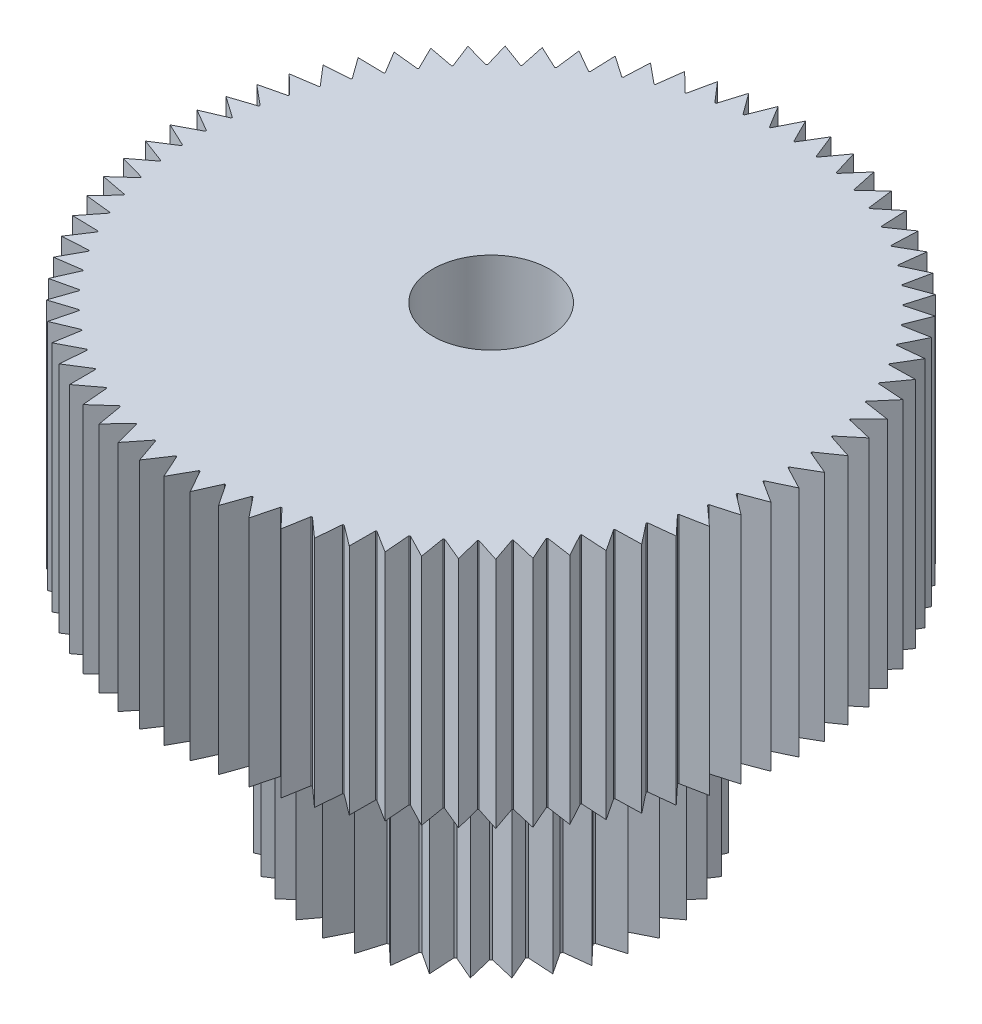
SolidWorks part; units mm, degrees
ref_plane "Front Plane" through (0, 0, 0) normal (0, 0, 1) x (1, 0, 0)
ref_plane "Top Plane" through (0, 0, 0) normal (0, 1, 0) x (1, 0, 0)
ref_plane "Right Plane" through (0, 0, 0) normal (1, 0, 0) x (0, 0, -1)
sketch "Sketch1" plane through (0, 0, 0) normal (0, 1, 0) x (1, 0, 0)
  circle A0 centre (0, 0) radius 5
  dimension "D1" = 10
extrude "Boss-Extrude1" add sketch "Sketch1" along normal blind 4
sketch "Sketch3" plane through (0, 4, 0) normal (0, 1, 0) x (1, 0, 0)
  line L0 (-0.2, 4.996) -> (0.2, 4.996)
  line L1 (-0.2, 4.996) -> (0, 5.396)
  line L2 (0, 5.396) -> (0.2, 4.996)
  line L3 (0.2188, 4.9952) -> (0.4515, 5.3771)
  line L4 (0.4515, 5.3771) -> (0.6174, 4.9617)
  line L5 (0.2188, 4.9952) -> (0.6174, 4.9617)
  line L6 (0.636, 4.9594) -> (0.8999, 5.3204)
  line L7 (0.8999, 5.3204) -> (1.0304, 4.8927)
  line L8 (0.636, 4.9594) -> (1.0304, 4.8927)
  line L9 (1.0487, 4.8888) -> (1.3419, 5.2265)
  line L10 (1.3419, 5.2265) -> (1.4362, 4.7893)
  line L11 (1.0487, 4.8888) -> (1.4362, 4.7893)
  line L12 (1.4541, 4.7839) -> (1.7746, 5.0959)
  line L13 (1.7746, 5.0959) -> (1.8319, 4.6523)
  line L14 (1.4541, 4.7839) -> (1.8319, 4.6523)
  line L15 (1.8493, 4.6454) -> (2.1948, 4.9295)
  line L16 (2.1948, 4.9295) -> (2.2148, 4.4827)
  line L17 (1.8493, 4.6454) -> (2.2148, 4.4827)
  line L18 (2.2316, 4.4744) -> (2.5995, 4.7285)
  line L19 (2.5995, 4.7285) -> (2.5821, 4.2817)
  line L20 (2.2316, 4.4744) -> (2.5821, 4.2817)
  line L21 (2.5982, 4.272) -> (2.9861, 4.4944)
  line L22 (2.9861, 4.4944) -> (2.9313, 4.0506)
  line L23 (2.5982, 4.272) -> (2.9313, 4.0506)
  line L24 (2.9465, 4.0396) -> (3.3517, 4.2288)
  line L25 (3.3517, 4.2288) -> (3.26, 3.7911)
  line L26 (2.9465, 4.0396) -> (3.26, 3.7911)
  line L27 (3.2742, 3.7788) -> (3.6938, 3.9335)
  line L28 (3.6938, 3.9335) -> (3.5658, 3.505)
  line L29 (3.2742, 3.7788) -> (3.5658, 3.505)
  line L30 (3.5789, 3.4916) -> (4.01, 3.6106)
  line L31 (4.01, 3.6106) -> (3.8466, 3.1943)
  line L32 (3.5789, 3.4916) -> (3.8466, 3.1943)
  line L33 (3.8585, 3.1799) -> (4.2981, 3.2624)
  line L34 (4.2981, 3.2624) -> (4.1004, 2.8613)
  line L35 (3.8585, 3.1799) -> (4.1004, 2.8613)
  line L36 (4.1111, 2.8459) -> (4.556, 2.8913)
  line L37 (4.556, 2.8913) -> (4.3254, 2.5081)
  line L38 (4.1111, 2.8459) -> (4.3254, 2.5081)
  line L39 (4.3348, 2.4919) -> (4.782, 2.4999)
  line L40 (4.782, 2.4999) -> (4.5201, 2.1374)
  line L41 (4.3348, 2.4919) -> (4.5201, 2.1374)
  line L42 (4.5281, 2.1204) -> (4.9744, 2.091)
  line L43 (4.9744, 2.091) -> (4.6831, 1.7517)
  line L44 (4.5281, 2.1204) -> (4.6831, 1.7517)
  line L45 (4.6897, 1.7341) -> (5.1319, 1.6675)
  line L46 (5.1319, 1.6675) -> (4.8133, 1.3536)
  line L47 (4.6897, 1.7341) -> (4.8133, 1.3536)
  line L48 (4.8183, 1.3356) -> (5.2534, 1.2322)
  line L49 (5.2534, 1.2322) -> (4.9097, 0.9461)
  line L50 (4.8183, 1.3356) -> (4.9097, 0.9461)
  line L51 (4.9132, 0.9277) -> (5.3381, 0.7883)
  line L52 (5.3381, 0.7883) -> (4.9716, 0.532)
  line L53 (4.9132, 0.9277) -> (4.9716, 0.532)
  line L54 (4.9736, 0.5133) -> (5.3854, 0.3388)
  line L55 (5.3854, 0.3388) -> (4.9987, 0.1141)
  line L56 (4.9736, 0.5133) -> (4.9987, 0.1141)
  line L57 (4.9991, 0.0953) -> (5.3948, -0.113)
  line L58 (5.3948, -0.113) -> (4.9907, -0.3046)
  line L59 (4.9991, 0.0953) -> (4.9907, -0.3046)
  line L60 (4.9895, -0.3233) -> (5.3664, -0.564)
  line L61 (5.3664, -0.564) -> (4.9477, -0.7211)
  line L62 (4.9895, -0.3233) -> (4.9477, -0.7211)
  line L63 (4.945, -0.7397) -> (5.3004, -1.0111)
  line L64 (5.3004, -1.0111) -> (4.87, -1.1326)
  line L65 (4.945, -0.7397) -> (4.87, -1.1326)
  line L66 (4.8657, -1.1509) -> (5.1972, -1.4511)
  line L67 (5.1972, -1.4511) -> (4.7582, -1.5362)
  line L68 (4.8657, -1.1509) -> (4.7582, -1.5362)
  line L69 (4.7524, -1.554) -> (5.0576, -1.8809)
  line L70 (5.0576, -1.8809) -> (4.6129, -1.9289)
  line L71 (4.7524, -1.554) -> (4.6129, -1.9289)
  line L72 (4.6057, -1.9462) -> (4.8824, -2.2975)
  line L73 (4.8824, -2.2975) -> (4.4354, -2.3082)
  line L74 (4.6057, -1.9462) -> (4.4354, -2.3082)
  line L75 (4.4267, -2.3248) -> (4.6731, -2.698)
  line L76 (4.6731, -2.698) -> (4.2267, -2.6712)
  line L77 (4.4267, -2.3248) -> (4.2267, -2.6712)
  line L78 (4.2166, -2.6871) -> (4.4309, -3.0796)
  line L79 (4.4309, -3.0796) -> (3.9883, -3.0155)
  line L80 (4.2166, -2.6871) -> (3.9883, -3.0155)
  line L81 (3.977, -3.0305) -> (4.1577, -3.4395)
  line L82 (4.1577, -3.4395) -> (3.722, -3.3387)
  line L83 (3.977, -3.0305) -> (3.722, -3.3387)
  line L84 (3.7094, -3.3526) -> (3.8553, -3.7754)
  line L85 (3.8553, -3.7754) -> (3.4296, -3.6384)
  line L86 (3.7094, -3.3526) -> (3.4296, -3.6384)
  line L87 (3.4159, -3.6513) -> (3.5259, -4.0847)
  line L88 (3.5259, -4.0847) -> (3.1131, -3.9126)
  line L89 (3.4159, -3.6513) -> (3.1131, -3.9126)
  line L90 (3.0984, -3.9243) -> (3.1717, -4.3655)
  line L91 (3.1717, -4.3655) -> (2.7748, -4.1594)
  line L92 (3.0984, -3.9243) -> (2.7748, -4.1594)
  line L93 (2.7591, -4.1698) -> (2.7953, -4.6155)
  line L94 (2.7953, -4.6155) -> (2.417, -4.377)
  line L95 (2.7591, -4.1698) -> (2.417, -4.377)
  line L96 (2.4005, -4.386) -> (2.3993, -4.8333)
  line L97 (2.3993, -4.8333) -> (2.0423, -4.5639)
  line L98 (2.4005, -4.386) -> (2.0423, -4.5639)
  line L99 (2.0251, -4.5715) -> (1.9864, -5.0171)
  line L100 (1.9864, -5.0171) -> (1.6532, -4.7188)
  line L101 (2.0251, -4.5715) -> (1.6532, -4.7188)
  line L102 (1.6355, -4.725) -> (1.5596, -5.1657)
  line L103 (1.5596, -5.1657) -> (1.2525, -4.8406)
  line L104 (1.6355, -4.725) -> (1.2525, -4.8406)
  line L105 (1.2344, -4.8452) -> (1.1219, -5.2781)
  line L106 (1.1219, -5.2781) -> (0.8431, -4.9284)
  line L107 (1.2344, -4.8452) -> (0.8431, -4.9284)
  line L108 (0.8246, -4.9315) -> (0.6763, -5.3534)
  line L109 (0.6763, -5.3534) -> (0.4277, -4.9817)
  line L110 (0.8246, -4.9315) -> (0.4277, -4.9817)
  line L111 (0.409, -4.9832) -> (0.226, -5.3913)
  line L112 (0.226, -5.3913) -> (0.0094, -5)
  line L113 (0.409, -4.9832) -> (0.0094, -5)
  line L114 (-0.0094, -5) -> (-0.226, -5.3913)
  line L115 (-0.226, -5.3913) -> (-0.409, -4.9832)
  line L116 (-0.0094, -5) -> (-0.409, -4.9832)
  line L117 (-0.4277, -4.9817) -> (-0.6763, -5.3534)
  line L118 (-0.6763, -5.3534) -> (-0.8246, -4.9315)
  line L119 (-0.4277, -4.9817) -> (-0.8246, -4.9315)
  line L120 (-0.8431, -4.9284) -> (-1.1219, -5.2781)
  line L121 (-1.1219, -5.2781) -> (-1.2344, -4.8452)
  line L122 (-0.8431, -4.9284) -> (-1.2344, -4.8452)
  line L123 (-1.2525, -4.8406) -> (-1.5596, -5.1657)
  line L124 (-1.5596, -5.1657) -> (-1.6355, -4.725)
  line L125 (-1.2525, -4.8406) -> (-1.6355, -4.725)
  line L126 (-1.6532, -4.7188) -> (-1.9864, -5.0171)
  line L127 (-1.9864, -5.0171) -> (-2.0251, -4.5715)
  line L128 (-1.6532, -4.7188) -> (-2.0251, -4.5715)
  line L129 (-2.0423, -4.5639) -> (-2.3993, -4.8333)
  line L130 (-2.3993, -4.8333) -> (-2.4005, -4.386)
  line L131 (-2.0423, -4.5639) -> (-2.4005, -4.386)
  line L132 (-2.417, -4.377) -> (-2.7953, -4.6155)
  line L133 (-2.7953, -4.6155) -> (-2.7591, -4.1698)
  line L134 (-2.417, -4.377) -> (-2.7591, -4.1698)
  line L135 (-2.7748, -4.1594) -> (-3.1717, -4.3655)
  line L136 (-3.1717, -4.3655) -> (-3.0984, -3.9243)
  line L137 (-2.7748, -4.1594) -> (-3.0984, -3.9243)
  line L138 (-3.1131, -3.9126) -> (-3.5259, -4.0847)
  line L139 (-3.5259, -4.0847) -> (-3.4159, -3.6513)
  line L140 (-3.1131, -3.9126) -> (-3.4159, -3.6513)
  line L141 (-3.4296, -3.6384) -> (-3.8553, -3.7754)
  line L142 (-3.8553, -3.7754) -> (-3.7094, -3.3526)
  line L143 (-3.4296, -3.6384) -> (-3.7094, -3.3526)
  line L144 (-3.722, -3.3387) -> (-4.1577, -3.4395)
  line L145 (-4.1577, -3.4395) -> (-3.977, -3.0305)
  line L146 (-3.722, -3.3387) -> (-3.977, -3.0305)
  line L147 (-3.9883, -3.0155) -> (-4.4309, -3.0796)
  line L148 (-4.4309, -3.0796) -> (-4.2166, -2.6871)
  line L149 (-3.9883, -3.0155) -> (-4.2166, -2.6871)
  line L150 (-4.2267, -2.6712) -> (-4.6731, -2.698)
  line L151 (-4.6731, -2.698) -> (-4.4267, -2.3248)
  line L152 (-4.2267, -2.6712) -> (-4.4267, -2.3248)
  line L153 (-4.4354, -2.3082) -> (-4.8824, -2.2975)
  line L154 (-4.8824, -2.2975) -> (-4.6057, -1.9462)
  line L155 (-4.4354, -2.3082) -> (-4.6057, -1.9462)
  line L156 (-4.6129, -1.9289) -> (-5.0576, -1.8809)
  line L157 (-5.0576, -1.8809) -> (-4.7524, -1.554)
  line L158 (-4.6129, -1.9289) -> (-4.7524, -1.554)
  line L159 (-4.7582, -1.5362) -> (-5.1972, -1.4511)
  line L160 (-5.1972, -1.4511) -> (-4.8657, -1.1509)
  line L161 (-4.7582, -1.5362) -> (-4.8657, -1.1509)
  line L162 (-4.87, -1.1326) -> (-5.3004, -1.0111)
  line L163 (-5.3004, -1.0111) -> (-4.945, -0.7397)
  line L164 (-4.87, -1.1326) -> (-4.945, -0.7397)
  line L165 (-4.9477, -0.7211) -> (-5.3664, -0.564)
  line L166 (-5.3664, -0.564) -> (-4.9895, -0.3233)
  line L167 (-4.9477, -0.7211) -> (-4.9895, -0.3233)
  line L168 (-4.9907, -0.3046) -> (-5.3948, -0.113)
  line L169 (-5.3948, -0.113) -> (-4.9991, 0.0953)
  line L170 (-4.9907, -0.3046) -> (-4.9991, 0.0953)
  line L171 (-4.9987, 0.1141) -> (-5.3854, 0.3388)
  line L172 (-5.3854, 0.3388) -> (-4.9736, 0.5133)
  line L173 (-4.9987, 0.1141) -> (-4.9736, 0.5133)
  line L174 (-4.9716, 0.532) -> (-5.3381, 0.7883)
  line L175 (-5.3381, 0.7883) -> (-4.9132, 0.9277)
  line L176 (-4.9716, 0.532) -> (-4.9132, 0.9277)
  line L177 (-4.9097, 0.9461) -> (-5.2534, 1.2322)
  line L178 (-5.2534, 1.2322) -> (-4.8183, 1.3356)
  line L179 (-4.9097, 0.9461) -> (-4.8183, 1.3356)
  line L180 (-4.8133, 1.3536) -> (-5.1319, 1.6675)
  line L181 (-5.1319, 1.6675) -> (-4.6897, 1.7341)
  line L182 (-4.8133, 1.3536) -> (-4.6897, 1.7341)
  line L183 (-4.6831, 1.7517) -> (-4.9744, 2.091)
  line L184 (-4.9744, 2.091) -> (-4.5281, 2.1204)
  line L185 (-4.6831, 1.7517) -> (-4.5281, 2.1204)
  line L186 (-4.5201, 2.1374) -> (-4.782, 2.4999)
  line L187 (-4.782, 2.4999) -> (-4.3348, 2.4919)
  line L188 (-4.5201, 2.1374) -> (-4.3348, 2.4919)
  line L189 (-4.3254, 2.5081) -> (-4.556, 2.8913)
  line L190 (-4.556, 2.8913) -> (-4.1111, 2.8459)
  line L191 (-4.3254, 2.5081) -> (-4.1111, 2.8459)
  line L192 (-4.1004, 2.8613) -> (-4.2981, 3.2624)
  line L193 (-4.2981, 3.2624) -> (-3.8585, 3.1799)
  line L194 (-4.1004, 2.8613) -> (-3.8585, 3.1799)
  line L195 (-3.8466, 3.1943) -> (-4.01, 3.6106)
  line L196 (-4.01, 3.6106) -> (-3.5789, 3.4916)
  line L197 (-3.8466, 3.1943) -> (-3.5789, 3.4916)
  line L198 (-3.5658, 3.505) -> (-3.6938, 3.9335)
  line L199 (-3.6938, 3.9335) -> (-3.2742, 3.7788)
  line L200 (-3.5658, 3.505) -> (-3.2742, 3.7788)
  line L201 (-3.26, 3.7911) -> (-3.3517, 4.2288)
  line L202 (-3.3517, 4.2288) -> (-2.9465, 4.0396)
  line L203 (-3.26, 3.7911) -> (-2.9465, 4.0396)
  line L204 (-2.9313, 4.0506) -> (-2.9861, 4.4944)
  line L205 (-2.9861, 4.4944) -> (-2.5982, 4.272)
  line L206 (-2.9313, 4.0506) -> (-2.5982, 4.272)
  line L207 (-2.5821, 4.2817) -> (-2.5995, 4.7285)
  line L208 (-2.5995, 4.7285) -> (-2.2316, 4.4744)
  line L209 (-2.5821, 4.2817) -> (-2.2316, 4.4744)
  line L210 (-2.2148, 4.4827) -> (-2.1948, 4.9295)
  line L211 (-2.1948, 4.9295) -> (-1.8493, 4.6454)
  line L212 (-2.2148, 4.4827) -> (-1.8493, 4.6454)
  line L213 (-1.8319, 4.6523) -> (-1.7746, 5.0959)
  line L214 (-1.7746, 5.0959) -> (-1.4541, 4.7839)
  line L215 (-1.8319, 4.6523) -> (-1.4541, 4.7839)
  line L216 (-1.4362, 4.7893) -> (-1.3419, 5.2265)
  line L217 (-1.3419, 5.2265) -> (-1.0487, 4.8888)
  line L218 (-1.4362, 4.7893) -> (-1.0487, 4.8888)
  line L219 (-1.0304, 4.8927) -> (-0.8999, 5.3204)
  line L220 (-0.8999, 5.3204) -> (-0.636, 4.9594)
  line L221 (-1.0304, 4.8927) -> (-0.636, 4.9594)
  line L222 (-0.6174, 4.9617) -> (-0.4515, 5.3771)
  line L223 (-0.4515, 5.3771) -> (-0.2188, 4.9952)
  line L224 (-0.6174, 4.9617) -> (-0.2188, 4.9952)
  circle A0 centre (0, 0) radius 5 construction
  point P231 (0, 0)
  dimension "D1" = 0.4
  dimension "D2" = 0.2
  dimension "D3" = 0.4
  dimension "D4" = 75
extrude "Boss-Extrude2" add sketch "Sketch3" against normal blind 4
sketch "Sketch4" plane through (0, 0, 0) normal (0, -1, 0) x (1, 0, 0)
  point P0 (0, 0)
sketch "Sketch5" plane through (0, 0, 0) normal (0, -1, 0) x (-1, 0, 0)
  circle A0 centre (0, 0) radius 2.5
  dimension "D1" = 5
extrude "Boss-Extrude3" add sketch "Sketch5" along normal blind 4 contours A0
sketch "Sketch6" plane through (0, -4, 0) normal (0, -1, 0) x (1, 0, 0)
  line L0 (-0.2, 2.492) -> (0.2, 2.492)
  line L1 (-0.2, 2.492) -> (0, 2.892)
  line L2 (0, 2.892) -> (0.2, 2.492)
  line L3 (0.2358, 2.4889) -> (0.5022, 2.8481)
  line L4 (0.5022, 2.8481) -> (0.6297, 2.4194)
  line L5 (0.2358, 2.4889) -> (0.6297, 2.4194)
  line L6 (0.6644, 2.4101) -> (0.9891, 2.7176)
  line L7 (0.9891, 2.7176) -> (1.0402, 2.2733)
  line L8 (0.6644, 2.4101) -> (1.0402, 2.2733)
  line L9 (1.0728, 2.2581) -> (1.446, 2.5045)
  line L10 (1.446, 2.5045) -> (1.4192, 2.0581)
  line L11 (1.0728, 2.2581) -> (1.4192, 2.0581)
  line L12 (1.4486, 2.0375) -> (1.8589, 2.2154)
  line L13 (1.8589, 2.2154) -> (1.755, 1.7804)
  line L14 (1.4486, 2.0375) -> (1.755, 1.7804)
  line L15 (1.7804, 1.755) -> (2.2154, 1.8589)
  line L16 (2.2154, 1.8589) -> (2.0375, 1.4486)
  line L17 (1.7804, 1.755) -> (2.0375, 1.4486)
  line L18 (2.0581, 1.4192) -> (2.5045, 1.446)
  line L19 (2.5045, 1.446) -> (2.2581, 1.0728)
  line L20 (2.0581, 1.4192) -> (2.2581, 1.0728)
  line L21 (2.2733, 1.0402) -> (2.7176, 0.9891)
  line L22 (2.7176, 0.9891) -> (2.4101, 0.6644)
  line L23 (2.2733, 1.0402) -> (2.4101, 0.6644)
  line L24 (2.4194, 0.6297) -> (2.8481, 0.5022)
  line L25 (2.8481, 0.5022) -> (2.4889, 0.2358)
  line L26 (2.4194, 0.6297) -> (2.4889, 0.2358)
  line L27 (2.492, 0.2) -> (2.892, 0)
  line L28 (2.892, 0) -> (2.492, -0.2)
  line L29 (2.492, 0.2) -> (2.492, -0.2)
  line L30 (2.4889, -0.2358) -> (2.8481, -0.5022)
  line L31 (2.8481, -0.5022) -> (2.4194, -0.6297)
  line L32 (2.4889, -0.2358) -> (2.4194, -0.6297)
  line L33 (2.4101, -0.6644) -> (2.7176, -0.9891)
  line L34 (2.7176, -0.9891) -> (2.2733, -1.0402)
  line L35 (2.4101, -0.6644) -> (2.2733, -1.0402)
  line L36 (2.2581, -1.0728) -> (2.5045, -1.446)
  line L37 (2.5045, -1.446) -> (2.0581, -1.4192)
  line L38 (2.2581, -1.0728) -> (2.0581, -1.4192)
  line L39 (2.0375, -1.4486) -> (2.2154, -1.8589)
  line L40 (2.2154, -1.8589) -> (1.7804, -1.755)
  line L41 (2.0375, -1.4486) -> (1.7804, -1.755)
  line L42 (1.755, -1.7804) -> (1.8589, -2.2154)
  line L43 (1.8589, -2.2154) -> (1.4486, -2.0375)
  line L44 (1.755, -1.7804) -> (1.4486, -2.0375)
  line L45 (1.4192, -2.0581) -> (1.446, -2.5045)
  line L46 (1.446, -2.5045) -> (1.0728, -2.2581)
  line L47 (1.4192, -2.0581) -> (1.0728, -2.2581)
  line L48 (1.0402, -2.2733) -> (0.9891, -2.7176)
  line L49 (0.9891, -2.7176) -> (0.6644, -2.4101)
  line L50 (1.0402, -2.2733) -> (0.6644, -2.4101)
  line L51 (0.6297, -2.4194) -> (0.5022, -2.8481)
  line L52 (0.5022, -2.8481) -> (0.2358, -2.4889)
  line L53 (0.6297, -2.4194) -> (0.2358, -2.4889)
  line L54 (0.2, -2.492) -> (0, -2.892)
  line L55 (0, -2.892) -> (-0.2, -2.492)
  line L56 (0.2, -2.492) -> (-0.2, -2.492)
  line L57 (-0.2358, -2.4889) -> (-0.5022, -2.8481)
  line L58 (-0.5022, -2.8481) -> (-0.6297, -2.4194)
  line L59 (-0.2358, -2.4889) -> (-0.6297, -2.4194)
  line L60 (-0.6644, -2.4101) -> (-0.9891, -2.7176)
  line L61 (-0.9891, -2.7176) -> (-1.0402, -2.2733)
  line L62 (-0.6644, -2.4101) -> (-1.0402, -2.2733)
  line L63 (-1.0728, -2.2581) -> (-1.446, -2.5045)
  line L64 (-1.446, -2.5045) -> (-1.4192, -2.0581)
  line L65 (-1.0728, -2.2581) -> (-1.4192, -2.0581)
  line L66 (-1.4486, -2.0375) -> (-1.8589, -2.2154)
  line L67 (-1.8589, -2.2154) -> (-1.755, -1.7804)
  line L68 (-1.4486, -2.0375) -> (-1.755, -1.7804)
  line L69 (-1.7804, -1.755) -> (-2.2154, -1.8589)
  line L70 (-2.2154, -1.8589) -> (-2.0375, -1.4486)
  line L71 (-1.7804, -1.755) -> (-2.0375, -1.4486)
  line L72 (-2.0581, -1.4192) -> (-2.5045, -1.446)
  line L73 (-2.5045, -1.446) -> (-2.2581, -1.0728)
  line L74 (-2.0581, -1.4192) -> (-2.2581, -1.0728)
  line L75 (-2.2733, -1.0402) -> (-2.7176, -0.9891)
  line L76 (-2.7176, -0.9891) -> (-2.4101, -0.6644)
  line L77 (-2.2733, -1.0402) -> (-2.4101, -0.6644)
  line L78 (-2.4194, -0.6297) -> (-2.8481, -0.5022)
  line L79 (-2.8481, -0.5022) -> (-2.4889, -0.2358)
  line L80 (-2.4194, -0.6297) -> (-2.4889, -0.2358)
  line L81 (-2.492, -0.2) -> (-2.892, 0)
  line L82 (-2.892, 0) -> (-2.492, 0.2)
  line L83 (-2.492, -0.2) -> (-2.492, 0.2)
  line L84 (-2.4889, 0.2358) -> (-2.8481, 0.5022)
  line L85 (-2.8481, 0.5022) -> (-2.4194, 0.6297)
  line L86 (-2.4889, 0.2358) -> (-2.4194, 0.6297)
  line L87 (-2.4101, 0.6644) -> (-2.7176, 0.9891)
  line L88 (-2.7176, 0.9891) -> (-2.2733, 1.0402)
  line L89 (-2.4101, 0.6644) -> (-2.2733, 1.0402)
  line L90 (-2.2581, 1.0728) -> (-2.5045, 1.446)
  line L91 (-2.5045, 1.446) -> (-2.0581, 1.4192)
  line L92 (-2.2581, 1.0728) -> (-2.0581, 1.4192)
  line L93 (-2.0375, 1.4486) -> (-2.2154, 1.8589)
  line L94 (-2.2154, 1.8589) -> (-1.7804, 1.755)
  line L95 (-2.0375, 1.4486) -> (-1.7804, 1.755)
  line L96 (-1.755, 1.7804) -> (-1.8589, 2.2154)
  line L97 (-1.8589, 2.2154) -> (-1.4486, 2.0375)
  line L98 (-1.755, 1.7804) -> (-1.4486, 2.0375)
  line L99 (-1.4192, 2.0581) -> (-1.446, 2.5045)
  line L100 (-1.446, 2.5045) -> (-1.0728, 2.2581)
  line L101 (-1.4192, 2.0581) -> (-1.0728, 2.2581)
  line L102 (-1.0402, 2.2733) -> (-0.9891, 2.7176)
  line L103 (-0.9891, 2.7176) -> (-0.6644, 2.4101)
  line L104 (-1.0402, 2.2733) -> (-0.6644, 2.4101)
  line L105 (-0.6297, 2.4194) -> (-0.5022, 2.8481)
  line L106 (-0.5022, 2.8481) -> (-0.2358, 2.4889)
  line L107 (-0.6297, 2.4194) -> (-0.2358, 2.4889)
  circle A0 centre (0, 0) radius 2.5 construction
  point P114 (0, 0)
  dimension "D1" = 0.4
  dimension "D2" = 0.2
  dimension "D3" = 0.4
  dimension "D4" = 36
extrude "Boss-Extrude4" add sketch "Sketch6" against normal blind 4
sketch "Sketch7" plane through (0, -4, 0) normal (0, -1, 0) x (-1, 0, 0)
  circle A3 centre (0, 0) radius 1
  dimension "D1" = 2
extrude "Cut-Extrude2" cut sketch "Sketch7" against normal through all
